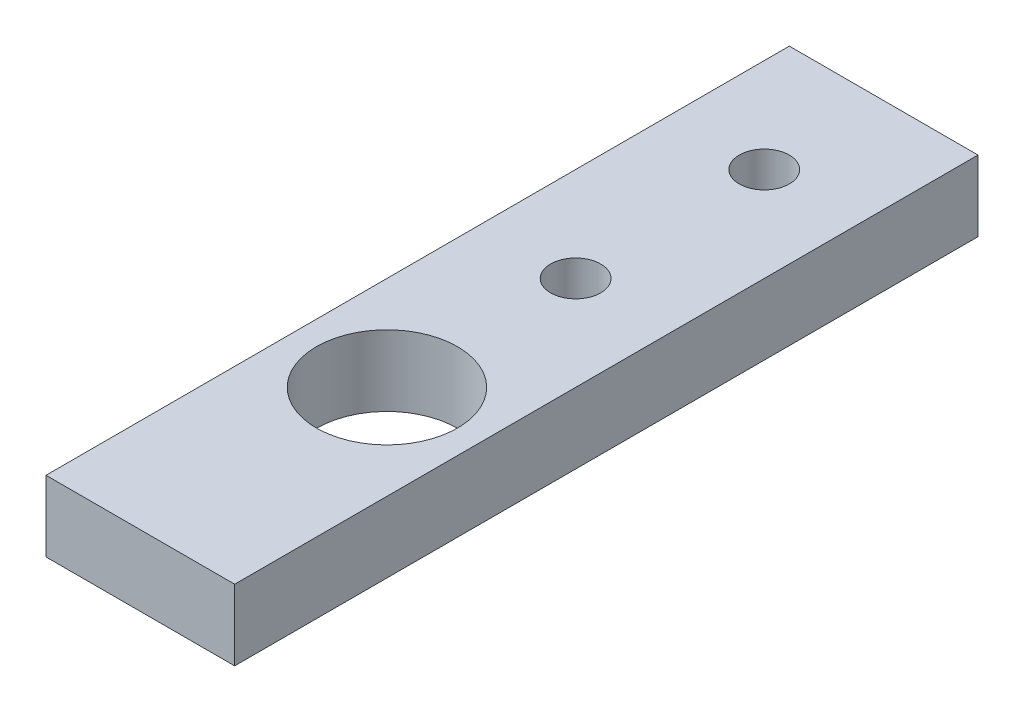
SolidWorks part; units mm, degrees
ref_plane "Front Plane" through (0, 0, 0) normal (0, 0, 1) x (1, 0, 0)
ref_plane "Top Plane" through (0, 0, 0) normal (0, 1, 0) x (1, 0, 0)
ref_plane "Right Plane" through (0, 0, 0) normal (1, 0, 0) x (0, 0, -1)
sketch "Sketch1" plane through (0, 0, 0) normal (0, 0, 1) x (1, 0, 0)
  line L1 (12.7, 4.7625) -> (-12.7, 4.7625)
  line L2 (12.7, 4.7625) -> (12.7, -4.7625)
  line L3 (12.7, -4.7625) -> (-12.7, -4.7625)
  line L4 (-12.7, 4.7625) -> (-12.7, -4.7625)
  line L5 (12.7, 4.7625) -> (-12.7, -4.7625) construction
  line L6 (12.7, -4.7625) -> (-12.7, 4.7625) construction
  point P0 (0, 0)
  dimension "D1" = 25.4
  dimension "D2" = 9.525
extrude "Boss-Extrude1" add sketch "Sketch1" along normal blind 100.076
sketch "Sketch2" plane through (0, 4.7625, 0) normal (0, 1, 0) x (1, 0, 0)
  line L0 (0, 0) -> (0, -100.076) construction
  line L1 (12.7, 0) -> (-12.7, 0) construction
  line L2 (12.7, -100.076) -> (-12.7, -100.076) construction
  circle A0 centre (0, -16.0734) radius 3.3734
  circle A1 centre (0, -41.4734) radius 3.3734
  circle A2 centre (0, -66.8734) radius 9.498
  point P12 (0, -12.7)
  dimension "D2" = 6.7469
  dimension "D3" = 18.996
  dimension "D1" = 25.4
  dimension "D4" = 25.4
  dimension "D5" = 12.7
extrude "Cut-Extrude1" cut sketch "Sketch2" against normal through all
